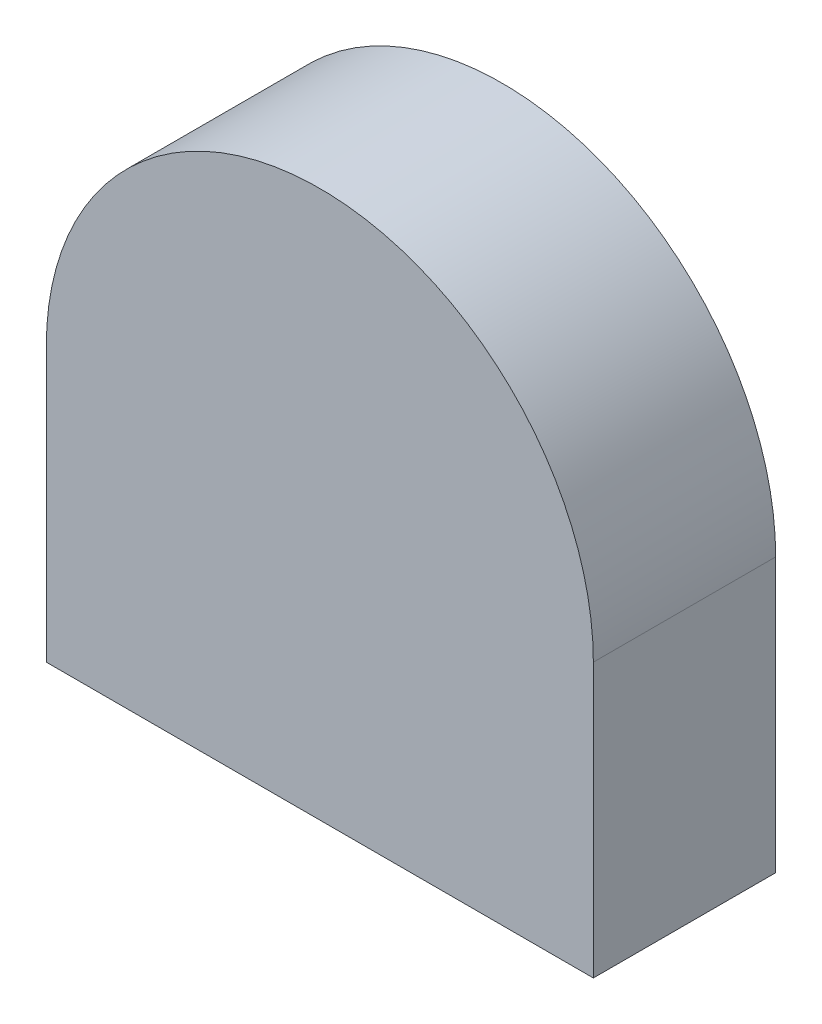
SolidWorks part; units mm, degrees
ref_plane "Front Plane" through (0, 0, 0) normal (0, 0, 1) x (1, 0, 0)
ref_plane "Top Plane" through (0, 0, 0) normal (0, 1, 0) x (1, 0, 0)
ref_plane "Right Plane" through (0, 0, 0) normal (1, 0, 0) x (0, 0, -1)
sketch "Sketch1" plane through (0, 0, 0) normal (0, 0, 1) x (1, 0, 0)
  line L1 (-8.5045, 28.4049) -> (10.5455, 28.4049)
  line L2 (-8.5045, 28.4049) -> (-8.5045, 18.8799)
  line L3 (-8.5045, 18.8799) -> (10.5455, 18.8799)
  line L4 (10.5455, 28.4049) -> (10.5455, 18.8799)
  arc A0 (-8.5045, 28.4049) -> (10.5455, 28.4049) centre (1.0205, 28.4049) cw
  dimension "D2" = 9.525
  dimension "D1" = 19.05
extrude "Boss-Extrude1" add sketch "Sketch1" along normal blind 6.35 contours A0 L1 | L4 L1 L2 L3
